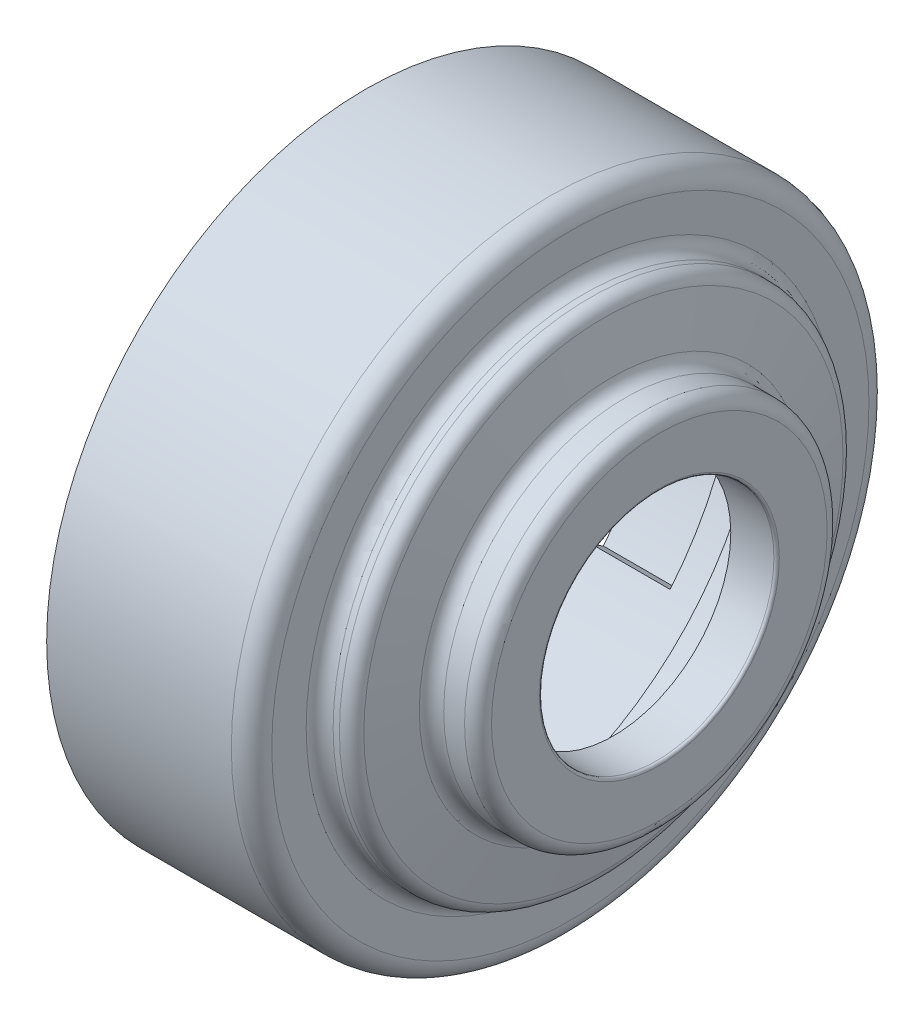
SolidWorks part; units mm, degrees
ref_plane "前视基准面" through (0, 0, 0) normal (0, 0, 1) x (1, 0, 0)
ref_plane "上视基准面" through (0, 0, 0) normal (0, 1, 0) x (1, 0, 0)
ref_plane "右视基准面" through (0, 0, 0) normal (1, 0, 0) x (0, 0, -1)
sketch "草图2" plane through (0, 0, 0) normal (0, 0, 1) x (1, 0, 0)
  line L0 (-36.9366, 0) -> (44.5849, 0) construction
  line L1 (0, 36.0368) -> (0, -37.1166) construction
  line L2 (-14, 22) -> (-6, 22)
  line L3 (-6, 22) -> (-6, 21.6)
  line L4 (-6, 21.6) -> (0, 21.6)
  line L5 (0, 21.6) -> (0, 17.4)
  line L6 (0, 17.4) -> (2.5, 17.4)
  line L8 (3.4081, 12.25) -> (6.6, 12.25)
  line L9 (6.6, 12.25) -> (6.6, 9.4)
  line L10 (6.6, 9.4) -> (4.4, 9.4)
  line L11 (4.4, 9.4) -> (4.4, 8.7)
  line L12 (4.4, 8.7) -> (7.8, 8.7)
  line L13 (-14, 22) -> (-14, 23.65)
  line L14 (-14, 23.65) -> (1.2, 23.65)
  line L15 (1.2, 23.65) -> (1.2, 18.6)
  line L16 (1.2, 18.6) -> (3.5069, 18.6)
  line L18 (4.415, 13.45) -> (7.8, 13.45)
  line L19 (7.8, 13.45) -> (7.8, 8.7)
  line L20 (2.5, 17.4) -> (3.4081, 12.25)
  line L21 (3.5069, 18.6) -> (4.415, 13.45)
  dimension "D1" = 44
  dimension "D2" = 0.4
  dimension "D3" = 8
  dimension "D4" = 14
  dimension "D5" = 34.8
  dimension "D6" = 2.5
  dimension "D7" = 18.8
  dimension "D8" = 0.7
  dimension "D9" = 4.4
  dimension "D10" = 2.2
  dimension "D11" = 24.5
  dimension "D12" = 47.3
  dimension "D13" = 2.05
  dimension "D14" = 1.2
  dimension "D15" = 10
  dimension "D16" = 1.2
  dimension "D17" = 1.2
  dimension "D18" = 1.2
  dimension "D19" = 1.2
  dimension "D20" = 1.65
revolve "旋转1" add sketch "草图2" angle 360 about L0
fillet "圆角1" radius 0.2 5 edges at (0, 0, 17.4) (0, 0, 21.6) (7.8, 0, 8.7) (6.6, 0, 12.25) (2.5, 0, 17.4)
fillet "圆角2" radius 1 4 edges at (1.2, 0, 18.6) (7.8, 0, 13.45) (3.5069, 0, 18.6) (4.415, 0, 13.45)
fillet "圆角3" radius 1.5 2 edges at (1.2, 0, 23.65) (3.4081, 0, 12.25)
sketch "草图3" plane through (-14, 0, 0) normal (-1, 0, 0) x (0, 0, 1)
  line L0 (0, 27.1942) -> (0, -25.474) construction
  line L1 (-27.7353, 0) -> (28.2343, 0) construction
  line L2 (-0.5, 22.6) -> (0.5, 22.6)
  line L3 (-0.5, 22.6) -> (-0.5, 21.9943)
  line L4 (0.5, 22.6) -> (0.5, 21.9943)
  circle A0 centre (0, 0) radius 22 construction
  arc A1 (0.5, 21.9943) -> (-0.5, 21.9943) centre (0, 0) ccw
  point P7 (0, 22)
  point P14 (0, 22.6)
  dimension "D1" = 1
  dimension "D2" = 0.6
extrude "切除-拉伸1" [suppressed] cut sketch "草图3" against normal blind 1
sketch "草图4" plane through (-14, 0, 0) normal (-1, 0, 0) x (0, 0, 1)
  line L0 (0, 29.159) -> (0, -31.1439) construction
  line L1 (-35.4917, 0) -> (32.6562, 0) construction
  line L2 (-3.75, 22.5402) -> (-3.75, 21.678)
  line L3 (3.75, 22.5402) -> (3.75, 21.678)
  circle A0 centre (0, 0) radius 22 construction
  arc A1 (3.75, 21.678) -> (-3.75, 21.678) centre (0, 0) ccw
  arc A2 (3.75, 22.5402) -> (-3.75, 22.5402) centre (0, 0) ccw
  dimension "D2" = 22.85
  dimension "D1" = 7.5
  dimension "D3" = 3.75
extrude "切除-拉伸2" cut sketch "草图4" against normal blind 5.7
sketch "草图5" plane through (0, 0, 0) normal (0, 0, 1) x (1, 0, 0)
  line L0 (16.6242, 0) -> (-23.7431, 0) construction
  line L1 (0, 27.01) -> (0, -27.8633) construction
  line L2 (-8.3, 22.85) -> (-8.3, 21.3419)
  line L3 (-8.3, 21.3419) -> (-10.7, 21.3419)
  line L4 (-10.7, 21.3419) -> (-10.7, 22.85)
  line L5 (-10.7, 22.85) -> (-8.3, 22.85)
  line L7 (-14, -0.161) -> (-14, 29.419) construction
  line L8 (-14, 21.678) -> (-14, -22) construction
  dimension "D1" = 3.3
  dimension "D2" = 2.4
  dimension "D3" = 45.7
revolve "切除-旋转1" cut sketch "草图5" angle 28 about L0
pattern_circular "阵列(圆周)1" count 3 over 360 about axis through (0, 0, 0) along (1, 0, 0) of "切除-拉伸2", "切除-旋转1"
